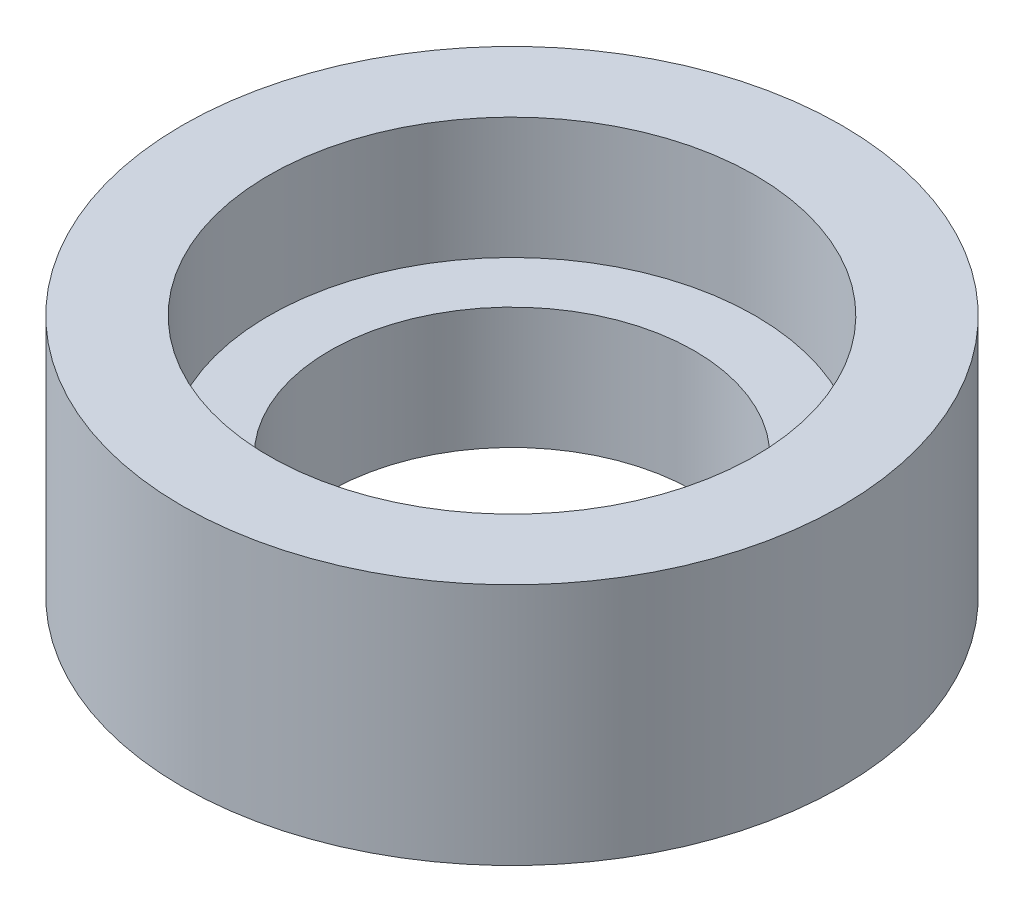
SolidWorks part; units mm, degrees
material "6061 Alloy"
ref_plane "Front Plane" through (0, 0, 0) normal (0, 0, 1) x (1, 0, 0)
ref_plane "Top Plane" through (0, 0, 0) normal (0, 1, 0) x (1, 0, 0)
ref_plane "Right Plane" through (0, 0, 0) normal (1, 0, 0) x (0, 0, -1)
sketch "Sketch1" plane through (0, 0, 0) normal (0, 0, 1) x (1, 0, 0)
  line L0 (0, 0) -> (0, 9.4829) construction
  line L1 (-4.3053, 3.175) -> (-4.3053, 0)
  line L2 (-4.3053, 0) -> (-2.3813, 0)
  line L3 (-2.3813, 0) -> (-2.3813, 1.5875)
  line L4 (-2.3813, 1.5875) -> (-3.175, 1.5875)
  line L5 (-3.175, 1.5875) -> (-3.175, 3.175)
  line L6 (-3.175, 3.175) -> (-4.3053, 3.175)
  dimension "D1" = 8.6106
  dimension "D2" = 6.35
  dimension "D3" = 4.7625
  dimension "D4" = 3.175
  dimension "D5" = 1.5875
revolve "Revolve1" add sketch "Sketch1" angle 360 about L0
ref_plane "Plane1" through (0, 0, 0) normal (-1, 0, 0) x (0, 0, -1)
ref_plane "Plane2" through (0, 0, 0) normal (-1, 0, 0) x (0, 0, -1)
ref_plane "Plane3" through (0, 0, 0) normal (-1, 0, 0) x (0, 0, -1)
